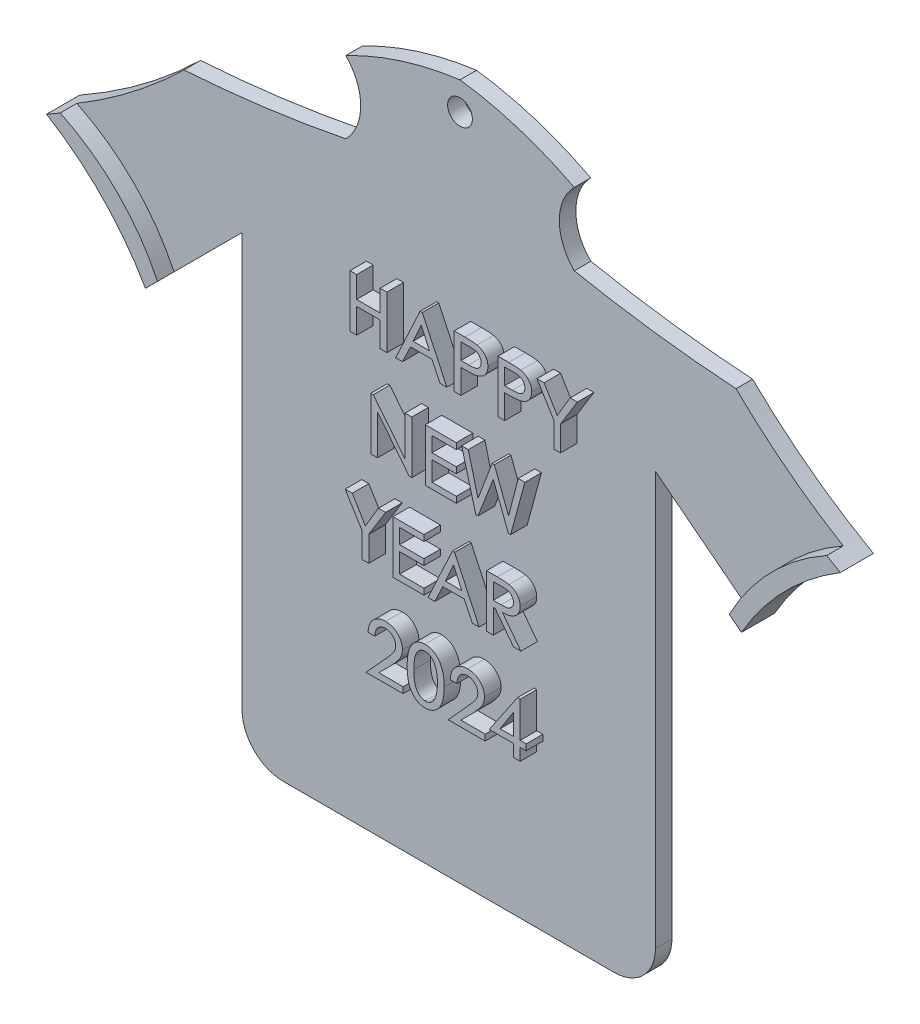
SolidWorks part; units mm, degrees
ref_plane "Front Plane" through (0, 0, 0) normal (0, 0, 1) x (1, 0, 0)
ref_plane "Top Plane" through (0, 0, 0) normal (0, 1, 0) x (1, 0, 0)
ref_plane "Right Plane" through (0, 0, 0) normal (1, 0, 0) x (0, 0, -1)
sketch "Sketch2" plane through (0, 0, 0) normal (0, 0, 1) x (1, 0, 0)
  line L0 (0, 55) -> (-9.6818, 45.3182)
  line L1 (5, 0) -> (45, 0)
  line L2 (0, 5) -> (0, 55)
  line L4 (50, 5) -> (50, 55)
  line L7 (50, 55) -> (62.4091, 45.3182)
  arc A0 (-21.6501, 57.5741) -> (-7.0267, 68.522) centre (-55.9313, 118.6053) ccw
  arc A1 (-9.6818, 45.3182) -> (-21.6501, 57.5741) centre (-39.3843, 28.2846) ccw
  arc A2 (74.3774, 57.5741) -> (59.7539, 68.522) centre (108.6586, 118.6053) cw
  arc A3 (62.4091, 45.3182) -> (74.3774, 57.5741) centre (92.1115, 28.2846) cw
  arc A4 (-7.0267, 68.522) -> (12.5455, 71.0909) centre (-17.0541, 220.7613) ccw
  arc A5 (12.5455, 71.0909) -> (12.5455, 79.8182) centre (8.1818, 75.4545) ccw
  arc A6 (12.5455, 79.8182) -> (26.3636, 84.1818) centre (31.7521, 43.0579) cw
  arc A7 (59.7539, 68.522) -> (40.1818, 71.0909) centre (69.7814, 220.7613) cw
  arc A8 (40.1818, 71.0909) -> (40.1818, 79.8182) centre (44.5455, 75.4545) cw
  arc A9 (40.1818, 79.8182) -> (26.3636, 84.1818) centre (20.9752, 43.0579) ccw
  arc A10 (5, 0) -> (0, 5) centre (5, 5) cw
  arc A11 (50, 5) -> (45, 0) centre (45, 5) cw
  point P29 (0, 0)
  point P32 (50, 0)
  dimension "D3" = 5
  dimension "D5" = 34.24
  dimension "D1" = 50
  dimension "D2" = 55
extrude "Boss-Extrude1" add sketch "Sketch2" along normal blind 5
sketch "Sketch4" plane through (0, 0, 5) normal (0, 0, 1) x (1, 0, 0)
  circle A0 centre (26.3636, 80.8155) radius 1.5
extrude "Cut-Extrude1" cut sketch "Sketch4" against normal blind 5
sketch "Sketch5" plane through (0, 0, 5) normal (0, 0, 1) x (1, 0, 0)
  text T0 "HAPPY\r\n NEW\r\nYEAR\r\n 2024" font "Century Gothic" height in points 24
extrude "Boss-Extrude2" add sketch "Sketch5" along normal blind 2
sketch "Sketch6" plane through (0, 0, 5) normal (0, 0, 1) x (1, 0, 0)
  line L0 (50, 55) -> (62.4091, 45.3182)
  line L1 (-9.6818, 45.3182) -> (0, 55)
  line L2 (59.7539, 68.522) -> (50, 55)
  line L3 (-7.0267, 68.522) -> (0, 55)
  arc A0 (62.4091, 45.3182) -> (74.3774, 57.5741) centre (92.1115, 28.2846) cw
  arc A1 (-9.6818, 45.3182) -> (-21.6501, 57.5741) centre (-39.3843, 28.2846) ccw
  arc A2 (59.7539, 68.522) -> (74.3774, 57.5741) centre (108.6586, 118.6053) ccw
  arc A3 (-21.6501, 57.5741) -> (-7.0267, 68.522) centre (-55.9313, 118.6053) ccw
  arc A4 (60.9337, 46.4693) -> (72.7208, 58.5346) centre (87.2178, 32.5815) cw
  arc A6 (-19.9936, 58.5346) -> (-8.2295, 46.7705) centre (-30.6925, 36.0716) cw
extrude "Boss-Extrude3" add sketch "Sketch6" along normal blind 2 contours A6 A3 A1 L1 | A4 L0 A0 A2
sketch "Sketch7" plane through (0, 0, 0) normal (0, 0, -1) x (-1, 0, 0)
  line L1 (0, 55) -> (0, 5)
  line L2 (-50, 55) -> (-50, 5)
  line L4 (-45, 0) -> (-5, 0)
  line L5 (0, 55) -> (9.6818, 45.3182)
  line L7 (-62.4091, 45.3182) -> (-50, 55)
  arc A0 (-5, 0) -> (0, 5) centre (-5, 5) ccw
  arc A1 (-50, 5) -> (-45, 0) centre (-45, 5) ccw
  arc A2 (9.6818, 45.3182) -> (21.6501, 57.5741) centre (39.3843, 28.2846) cw
  arc A3 (-74.3774, 57.5741) -> (-62.4091, 45.3182) centre (-92.1115, 28.2846) cw
  arc A4 (-74.3774, 57.5741) -> (-59.7539, 68.522) centre (-108.6586, 118.6053) ccw
  arc A5 (7.0267, 68.522) -> (21.6501, 57.5741) centre (55.9313, 118.6053) ccw
  arc A6 (-12.5455, 79.8182) -> (-12.5455, 71.0909) centre (-8.1818, 75.4545) ccw
  arc A7 (-40.1818, 79.8182) -> (-40.1818, 71.0909) centre (-44.5455, 75.4545) cw
  arc A8 (-40.1818, 79.8182) -> (-26.3636, 84.1818) centre (-20.9752, 43.0579) cw
  arc A9 (-26.3636, 84.1818) -> (-12.5455, 79.8182) centre (-31.7521, 43.0579) cw
  arc A10 (-59.7539, 68.522) -> (-40.1818, 71.0909) centre (-69.7814, 220.7613) ccw
  arc A11 (-12.5455, 71.0909) -> (7.0267, 68.522) centre (17.0541, 220.7613) ccw
extrude "Cut-Extrude2" cut sketch "Sketch7" against normal blind 3
sketch "Sketch8" plane through (0, 0, 3) normal (0, 0, -1) x (-1, 0, 0)
  line L0 (0, 55) -> (0, 5)
  line L1 (0, 5) -> (0, 55) construction
  line L2 (-50, 55) -> (-50, 5)
  line L3 (-50, 55) -> (-50, 5) construction
  line L4 (-45, 0) -> (-5, 0)
  line L5 (0, 55) -> (9.6818, 45.3182)
  line L6 (-62.4091, 45.3182) -> (-50, 55)
  arc A0 (-5, 0) -> (0, 5) centre (-5, 5) ccw construction
  arc A1 (-50, 5) -> (-45, 0) centre (-45, 5) ccw construction
  arc A2 (-5, 0) -> (0, 5) centre (-5, 5) ccw
  arc A3 (-45, 0) -> (-50, 5) centre (-45, 5) cw
  arc A4 (-74.3774, 57.5741) -> (-62.4091, 45.3182) centre (-92.1115, 28.2846) cw
  arc A5 (9.6818, 45.3182) -> (21.6501, 57.5741) centre (39.3843, 28.2846) cw
  arc A6 (7.0267, 68.522) -> (21.6501, 57.5741) centre (55.9313, 118.6053) ccw
  arc A7 (-74.3774, 57.5741) -> (-59.7539, 68.522) centre (-108.6586, 118.6053) ccw
  arc A8 (-59.7539, 68.522) -> (-40.1818, 71.0909) centre (-69.7814, 220.7613) ccw
  arc A9 (-12.5455, 71.0909) -> (7.0267, 68.522) centre (17.0541, 220.7613) ccw
  arc A10 (-12.5455, 79.8182) -> (-12.5455, 71.0909) centre (-8.1818, 75.4545) ccw
  arc A11 (-40.1818, 79.8182) -> (-40.1818, 71.0909) centre (-44.5455, 75.4545) cw
  arc A12 (-40.1818, 79.8182) -> (-26.3636, 84.1818) centre (-20.9752, 43.0579) cw
  arc A13 (-26.3636, 84.1818) -> (-12.5455, 79.8182) centre (-31.7521, 43.0579) cw
  dimension "D2" = 5
  dimension "D3" = 34.24
  dimension "D4" = 70
  dimension "D5" = 152.5692
  dimension "D6" = 41.4755
  dimension "D7" = 41.4755
  dimension "D8" = 6.1711
  dimension "D1" = 50
  dimension "D9" = 40
